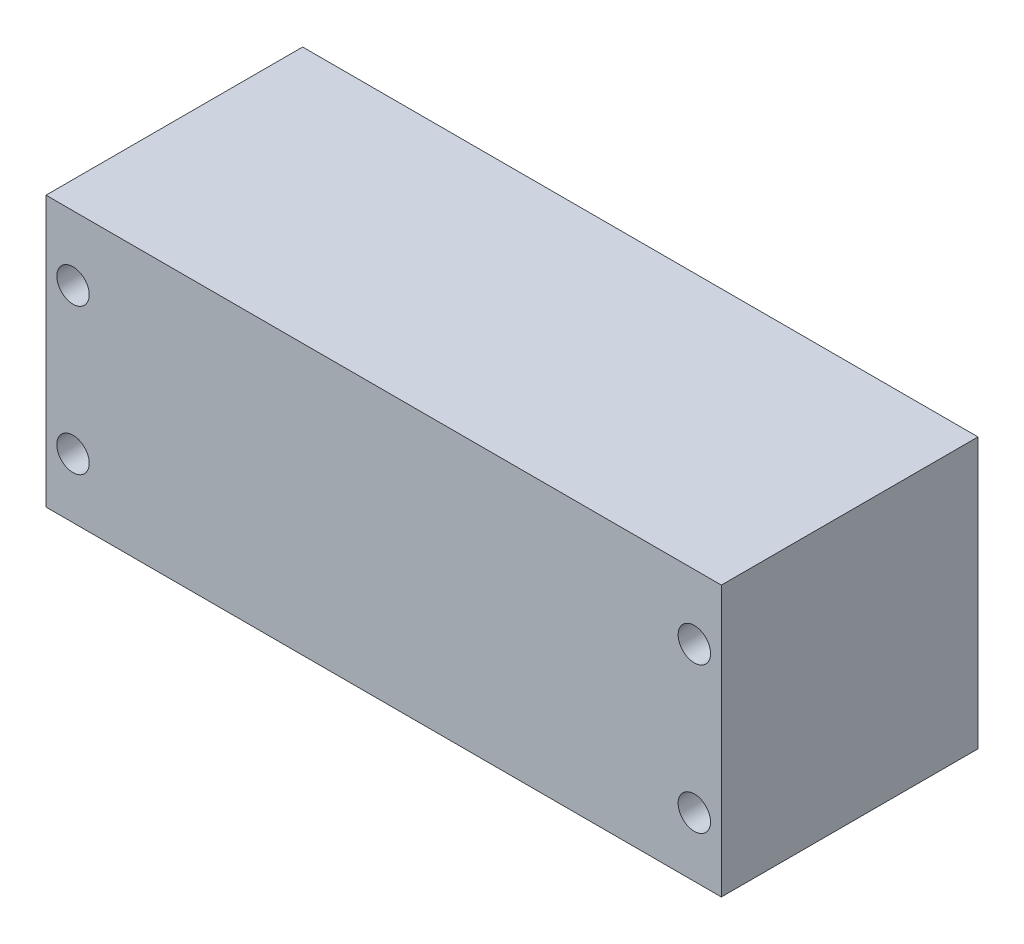
SolidWorks part; units mm, degrees
ref_plane "Front Plane" through (0, 0, 0) normal (0, 0, 1) x (1, 0, 0)
ref_plane "Top Plane" through (0, 0, 0) normal (0, 1, 0) x (1, 0, 0)
ref_plane "Right Plane" through (0, 0, 0) normal (1, 0, 0) x (0, 0, -1)
sketch "Sketch1" plane through (0, 0, 0) normal (0, 0, 1) x (1, 0, 0)
  line L1 (-33.75, 21.5625) -> (66.25, 21.5625)
  line L2 (-33.75, 21.5625) -> (-33.75, -18.4375)
  line L3 (-33.75, -18.4375) -> (66.25, -18.4375)
  line L4 (66.25, 21.5625) -> (66.25, -18.4375)
  dimension "D1" = 100
  dimension "D2" = 40
extrude "Boss-Extrude1" add sketch "Sketch1" along normal blind 38
sketch "Sketch2" plane through (0, 0, 0) normal (0, 0, -1) x (-1, 0, 0)
  line L0 (-66.25, -18.4375) -> (-66.25, 21.5625) construction
  line L1 (-58.25, 18.5625) -> (-18.75, 18.5625)
  line L2 (-58.25, 18.5625) -> (-58.25, -15.4375)
  line L3 (-58.25, -15.4375) -> (-18.75, -15.4375)
  line L4 (-18.75, 18.5625) -> (-18.75, -15.4375)
  line L5 (-13.75, 18.5625) -> (25.75, 18.5625)
  line L6 (-13.75, 18.5625) -> (-13.75, -15.4375)
  line L7 (-13.75, -15.4375) -> (25.75, -15.4375)
  line L8 (25.75, 18.5625) -> (25.75, -15.4375)
  line L9 (33.75, 21.5625) -> (33.75, -18.4375) construction
  line L10 (-66.25, 21.5625) -> (33.75, 21.5625) construction
  line L11 (33.75, -18.4375) -> (-66.25, -18.4375) construction
  dimension "D1" = 8
  dimension "D2" = 8
  dimension "D3" = 5
  dimension "D4" = 3
  dimension "D5" = 3
  dimension "D6" = 3
  dimension "D7" = 3
  dimension "D8" = 39.5
  dimension "D9" = 39.5
extrude "Cut-Extrude2" cut sketch "Sketch2" against normal blind 21 from offset 12 offset against normal yes
sketch "Sketch3" plane through (-3.3623, 0, 0) normal (0, 0, -1) x (-1, 0, 0)
  arc A0 (-55.6418, 7.0775) -> (16.2528, 4.0018) centre (-18.1567, 41.487) ccw construction
  arc A1 (-61.5934, 1.6143) -> (21.716, -1.9497) centre (-18.1567, 41.487) ccw
  arc A2 (-49.6903, 12.5407) -> (10.7896, 9.9533) centre (-18.1567, 41.487) ccw
  arc A3 (-49.6903, 12.5407) -> (-61.5934, 1.6143) centre (-55.6418, 7.0775) ccw
  arc A4 (21.716, -1.9497) -> (10.7896, 9.9533) centre (16.2528, 4.0018) ccw
  point P3 (-20.3315, -9.3502)
extrude "Cut-Extrude3" cut sketch "Sketch3" against normal blind 9 contours A2 A4 A1 A3
sketch "Sketch4" plane through (0, 0, 0) normal (0, 0, -1) x (-1, 0, 0)
  line L0 (-66.25, -18.4375) -> (-66.25, 21.5625) construction
  line L1 (33.75, 21.5625) -> (33.75, -18.4375) construction
  circle A0 centre (-62.25, 11.9848) radius 2.4
  circle A1 centre (-62.25, -9.6166) radius 2.4
  circle A2 centre (29.75, 11.9848) radius 2.4
  circle A3 centre (29.75, -9.6166) radius 2.4
  point P8 (0, 0)
  point P9 (0, 0)
  point P10 (0, 0)
  point P11 (0, 0)
  point P12 (0, 0)
  point P13 (0, 0)
  point P14 (-62.8335, 11.9848)
  point P17 (0, 0)
  point P18 (0, 0)
  point P21 (0, 0)
  dimension "D1" = 4
  dimension "D2" = 4
extrude "Cut-Extrude4" cut sketch "Sketch4" against normal up to next
